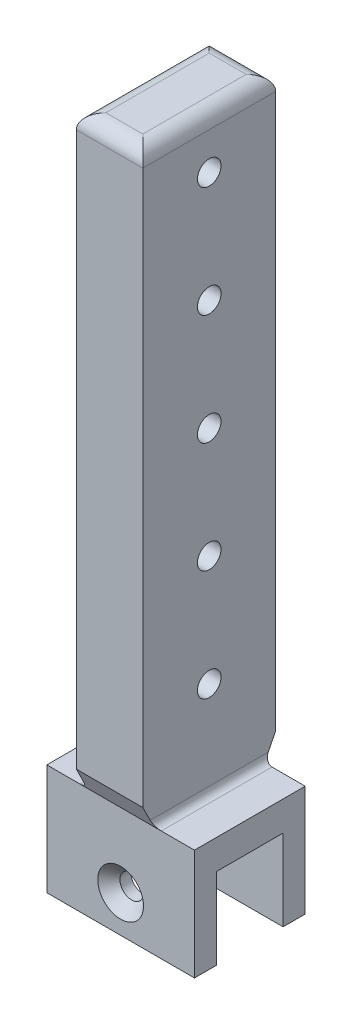
SolidWorks part; units mm, degrees
material "PLA"
ref_plane "Front Plane" through (0, 0, 0) normal (0, 0, 1) x (1, 0, 0)
ref_plane "Top Plane" through (0, 0, 0) normal (0, 1, 0) x (1, 0, 0)
ref_plane "Right Plane" through (0, 0, 0) normal (1, 0, 0) x (0, 0, -1)
sketch "Sketch1" plane through (0, 0, 0) normal (0, 1, 0) x (1, 0, 0)
  line L1 (0, 0) -> (-9, 0)
  line L2 (0, 0) -> (0, 18)
  line L3 (0, 18) -> (-9, 18)
  line L4 (-9, 0) -> (-9, 18)
  dimension "D1" = 9
  dimension "D2" = 18
extrude "Boss-Extrude1" add sketch "Sketch1" along normal blind 80
sketch "Sketch2" plane through (0, 0, 0) normal (0, -1, 0) x (1, 0, 0)
  line L1 (-14.5, -1.5) -> (5.5, -1.5)
  line L2 (-14.5, -1.5) -> (-14.5, -16.5)
  line L3 (-14.5, -16.5) -> (5.5, -16.5)
  line L4 (5.5, -1.5) -> (5.5, -16.5)
  line L5 (-9, -9) -> (1.8767, -9) construction
  line L6 (-9, -18) -> (-9, 0) construction
  line L7 (-4.5, -18) -> (-4.5, 2.9687) construction
  line L8 (0, -18) -> (-9, -18) construction
  dimension "D1" = 7.5
  dimension "D2" = 7.5
  dimension "D3" = 10
  dimension "D4" = 10
extrude "Boss-Extrude2" add sketch "Sketch2" along normal blind 15
sketch "Sketch4" plane through (5.5, 0, 0) normal (1, 0, 0) x (0, 0, -1)
  line L0 (13.5, -15) -> (13.5, -4)
  line L1 (16.5, -15) -> (1.5, -15) construction
  line L2 (13.5, -4) -> (4.5, -4)
  line L3 (4.5, -4) -> (4.5, -15)
  line L4 (4.5, -15) -> (13.5, -15)
  line L5 (9, 0) -> (9, 13.9433) construction
  line L6 (16.5, 0) -> (1.5, 0) construction
  line L7 (1.5, 0) -> (16.5, 0) construction
  dimension "D1" = 4.5
  dimension "D2" = 4.5
  dimension "D3" = 4
extrude "Cut-Extrude2" cut sketch "Sketch4" against normal blind 20
sketch "Sketch5" plane through (0, 0, -16.5) normal (0, 0, -1) x (-1, 0, 0)
  line L0 (4.5, 0) -> (4.5, 21.4418) construction
  line L1 (0, 0) -> (9, 0) construction
  line L3 (14.5, -15) -> (-5.5, -15) construction
  circle A0 centre (4.5, -10) radius 1.6
  dimension "D2" = 3.2
  dimension "D1" = 5
extrude "Cut-Extrude3" cut sketch "Sketch5" against normal blind 20
fillet "Fillet3" radius 2 4 edges at (-4.5, 80, 0) (0, 80, -9) (-9, 80, -9) (-4.5, 80, -18)
sketch "Sketch6" plane through (0, 0, 0) normal (1, 0, 0) x (0, 0, -1)
  line L1 (9, 78) -> (9, -8.2791) construction
  line L2 (18, 78) -> (0, 78) construction
  circle A0 centre (9, 73) radius 1.6
  circle A1 centre (9, 58) radius 1.6
  circle A2 centre (9, 43) radius 1.6
  circle A3 centre (9, 28) radius 1.6
  circle A4 centre (9, 13) radius 1.6
  dimension "D1" = 3.2
  dimension "D2" = 3.2
  dimension "D3" = 3.2
  dimension "D4" = 3.2
  dimension "D5" = 3.2
  dimension "D6" = 15
  dimension "D7" = 15
  dimension "D8" = 15
  dimension "D9" = 15
  dimension "D10" = 5
extrude "Cut-Extrude4" cut sketch "Sketch6" against normal blind 10
sketch "Sketch7" plane through (-9, 0, 0) normal (-1, 0, 0) x (0, 0, 1)
  line L0 (-16.5, 0) -> (-18, 3)
  line L1 (-18, 78) -> (-18, 0) construction
  line L2 (-1.5, 0) -> (0, 3)
  line L3 (0, 78) -> (0, 0) construction
  line L4 (-18, 0) -> (-16.5, 0) construction
  line L5 (-18, 3) -> (-18, 0)
  line L6 (-18, 0) -> (-16.5, 0)
  line L7 (-1.5, 0) -> (0, 0)
  line L8 (0, 0) -> (0, 3)
  dimension "D1" = 3
  dimension "D2" = 3
extrude "Cut-Extrude5" cut sketch "Sketch7" against normal blind 10
fillet "Fillet8" radius 1 2 edges at (0, 0, -9) (-9, 0, -9)
chamfer "Chamfer1" distance 1.5 angle 45 1 edges at (-6.1, -10, -1.5)
